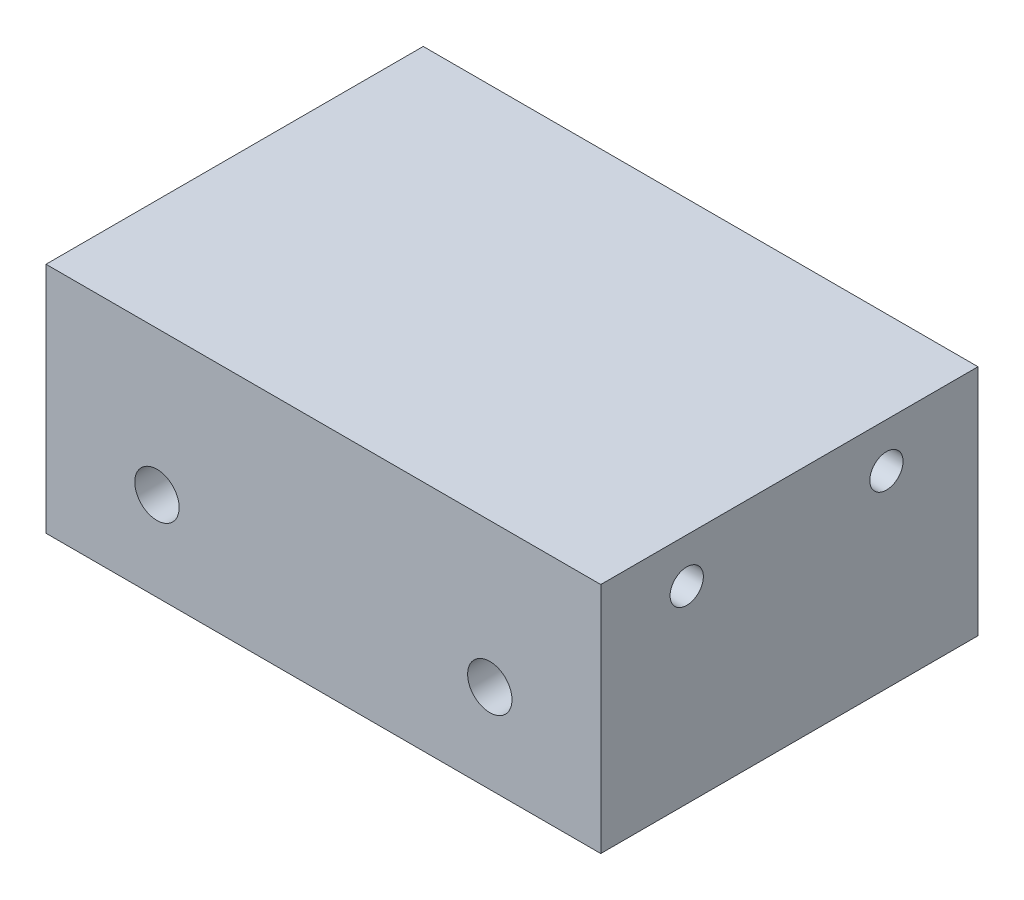
SolidWorks part; units mm, degrees
ref_plane "Front" through (0, 0, 0) normal (0, 0, 1) x (1, 0, 0)
ref_plane "Top" through (0, 0, 0) normal (0, 1, 0) x (1, 0, 0)
ref_plane "Right" through (0, 0, 0) normal (1, 0, 0) x (0, 0, -1)
sketch "草图1" plane through (0, 0, 0) normal (0, 0, 1) x (1, 0, 0)
  line L0 (35, -3) -> (-25, -3) construction
  line L1 (25, -3) -> (-25, -3)
  line L2 (25, -24) -> (25, 0) construction
  line L3 (-25, -24) -> (25, -24) construction
  line L4 (-25, -24) -> (-25, 0) construction
  line L5 (25, -24) -> (25, -3)
  line L6 (-25, -24) -> (25, -24)
  line L7 (-25, -24) -> (-25, -3)
  point P5 (25, -3)
extrude "凸台-拉伸1" add sketch "草图1" along normal up to surface (34 mm away) contours L6 L5 L1 L7
sketch "草图2" plane through (0, 0, 0) normal (0, 0, -1) x (-1, 0, 0)
  circle A0 centre (-15, -16) radius 2 construction
  circle A1 centre (15, -16) radius 2 construction
  circle A2 centre (-15, -16) radius 2
  circle A3 centre (15, -16) radius 2
extrude "切除-拉伸1" cut sketch "草图2" against normal through all
sketch "草图3" plane through (-25, 0, 0) normal (-1, 0, 0) x (0, 0, 1)
  circle A0 centre (8.2526, -7) radius 1.5 construction
  circle A1 centre (26.2526, -7) radius 1.5 construction
  circle A2 centre (8.2526, -7) radius 1.5
  circle A3 centre (26.2526, -7) radius 1.5
extrude "切除-拉伸2" cut sketch "草图3" against normal through all
